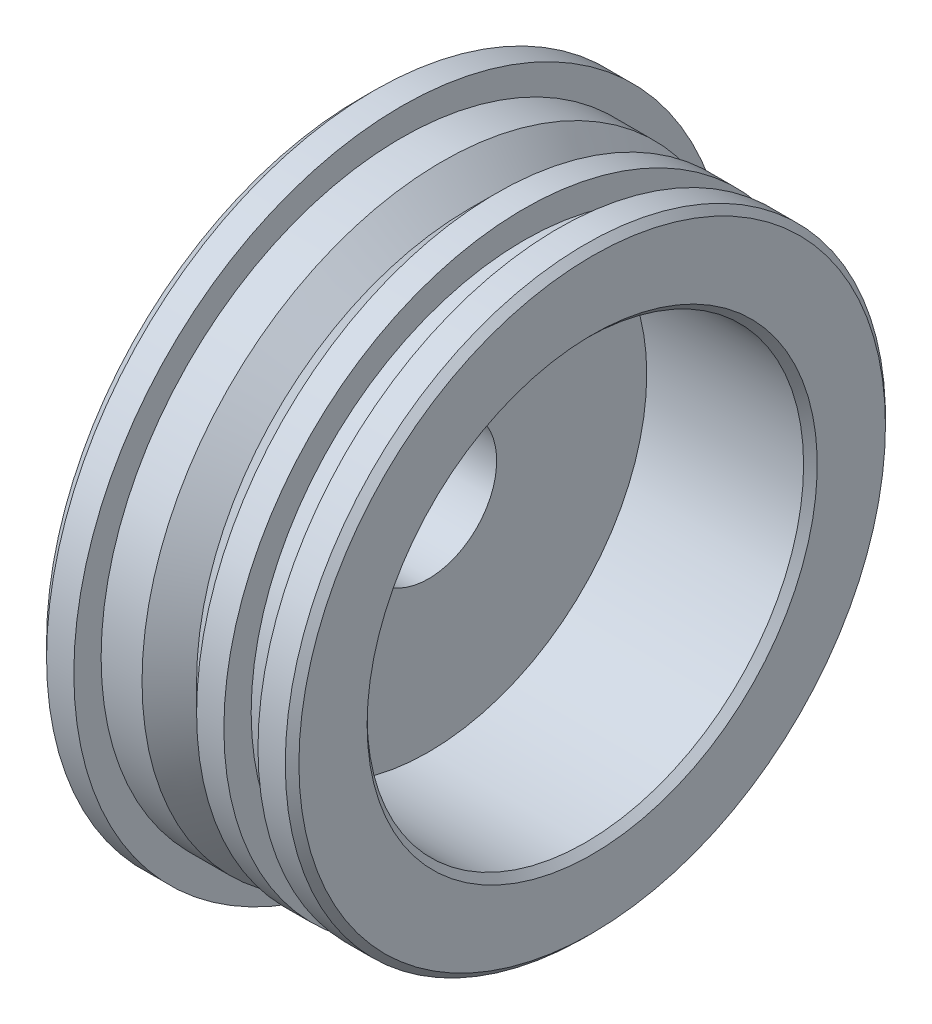
SolidWorks part; units mm, degrees
material "1060 Сплав"
ref_plane "Спереди" through (0, 0, 0) normal (0, 0, 1) x (1, 0, 0)
ref_plane "Сверху" through (0, 0, 0) normal (0, 1, 0) x (1, 0, 0)
ref_plane "Справа" through (0, 0, 0) normal (1, 0, 0) x (0, 0, -1)
sketch "Эскиз1" plane through (0, 0, 0) normal (0, 0, 1) x (1, 0, 0)
  line L0 (0, 0) -> (75.9362, 0) construction
  line L1 (-5, 0) -> (-5, 23)
  line L2 (-4, 24) -> (-2, 24)
  line L3 (-2, 24) -> (-2, 22)
  line L4 (-2, 22) -> (1, 22)
  line L5 (1, 22) -> (3, 20)
  line L6 (3, 20) -> (5, 22)
  line L7 (5, 22) -> (7, 22)
  line L8 (7, 22) -> (7, 20)
  line L9 (7, 20) -> (9.5, 20)
  line L10 (9.5, 20) -> (9.5, 22)
  line L11 (9.5, 22) -> (11.5, 22)
  line L12 (12, 21.5) -> (12, 16.5)
  line L13 (11.5, 16) -> (0, 16)
  line L14 (0, 16) -> (0, 0)
  line L15 (-5, 23) -> (-4, 24)
  line L16 (11.5, 22) -> (12, 21.5)
  line L17 (12, 16.5) -> (11.5, 16)
  line L18 (-5, 0) -> (0, 0)
  point P5 (-5, 24)
  point P16 (12, 22)
  point P17 (12, 16)
  dimension "D1" = 135
  dimension "D2" = 2
  dimension "D3" = 3
  dimension "D4" = 2.5
  dimension "D5" = 6
  dimension "D6" = 2
  dimension "D7" = 5
  dimension "D8" = 2
  dimension "D9" = 2.5
  dimension "D10" = 2
  dimension "D11" = 48
  dimension "D12" = 5
revolve "Повернуть1" add sketch "Эскиз1" angle 360 about L0
sketch "Эскиз2" plane through (-5, 0, 0) normal (-1, 0, 0) x (0, 0, 1)
  circle A0 centre (0, 0) radius 5
  dimension "D1" = 10
extrude "Вырез-Вытянуть1" cut sketch "Эскиз2" against normal blind 10
